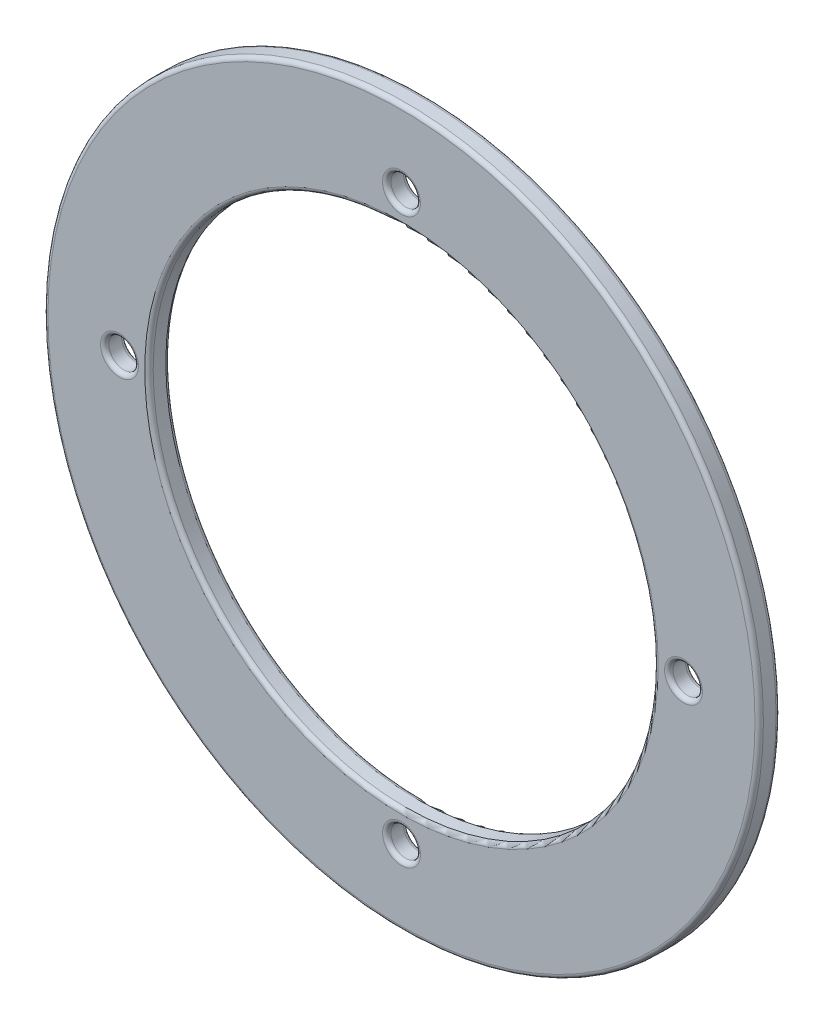
SolidWorks part; units mm, degrees
ref_plane "Front Plane" through (0, 0, 0) normal (0, 0, 1) x (1, 0, 0)
ref_plane "Top Plane" through (0, 0, 0) normal (0, 1, 0) x (1, 0, 0)
ref_plane "Right Plane" through (0, 0, 0) normal (1, 0, 0) x (0, 0, -1)
sketch "Sketch1" plane through (0, 0, 0) normal (0, 0, 1) x (1, 0, 0)
  line L0 (0, 0) -> (0, 33.5) construction
  line L1 (0, 33.5) -> (0, 42.5) construction
  circle A0 centre (0, 0) radius 42.5
  circle A1 centre (0, 0) radius 2.25
  circle A2 centre (0, 33.5) radius 1.75
  circle A3 centre (33.5, 0) radius 1.75
  circle A4 centre (0, -33.5) radius 1.75
  circle A5 centre (-33.5, 0) radius 1.75
  point P16 (0, 0)
  dimension "D1" = 3.5
  dimension "D2" = 4.5
  dimension "D3" = 85
  dimension "D4" = 33.5
  dimension "D5" = 4
extrude "Boss-Extrude1" add sketch "Sketch1" along normal blind 2.5
sketch "Sketch2" plane through (0, 0, 0) normal (0, 0, -1) x (-1, 0, 0)
  circle A0 centre (0, 0) radius 29.85
  circle A1 centre (0, 0) radius 12.65
  dimension "D1" = 59.7
  dimension "D2" = 25.3
extrude "Boss-Extrude2" add sketch "Sketch2" along normal blind 1
sketch "Sketch3" plane through (0, 0, 0) normal (0, 0, 1) x (1, 0, 0)
  circle A0 centre (0, 0) radius 30
  dimension "D1" = 60
extrude "Cut-Extrude1" cut sketch "Sketch3" along normal through all both and the other way through all
fillet "Fillet1" radius 0.5 12 edges at (30, 0, 2.5) (30, 0, 0) (-31.75, 0, 0) (-31.75, 0, 2.5) (1.75, -33.5, 0) (1.75, -33.5, 2.5) (35.25, 0, 0) (35.25, 0, 2.5) (1.75, 33.5, 0) (1.75, 33.5, 2.5) (42.5, 0, 2.5) (42.5, 0, 0)
